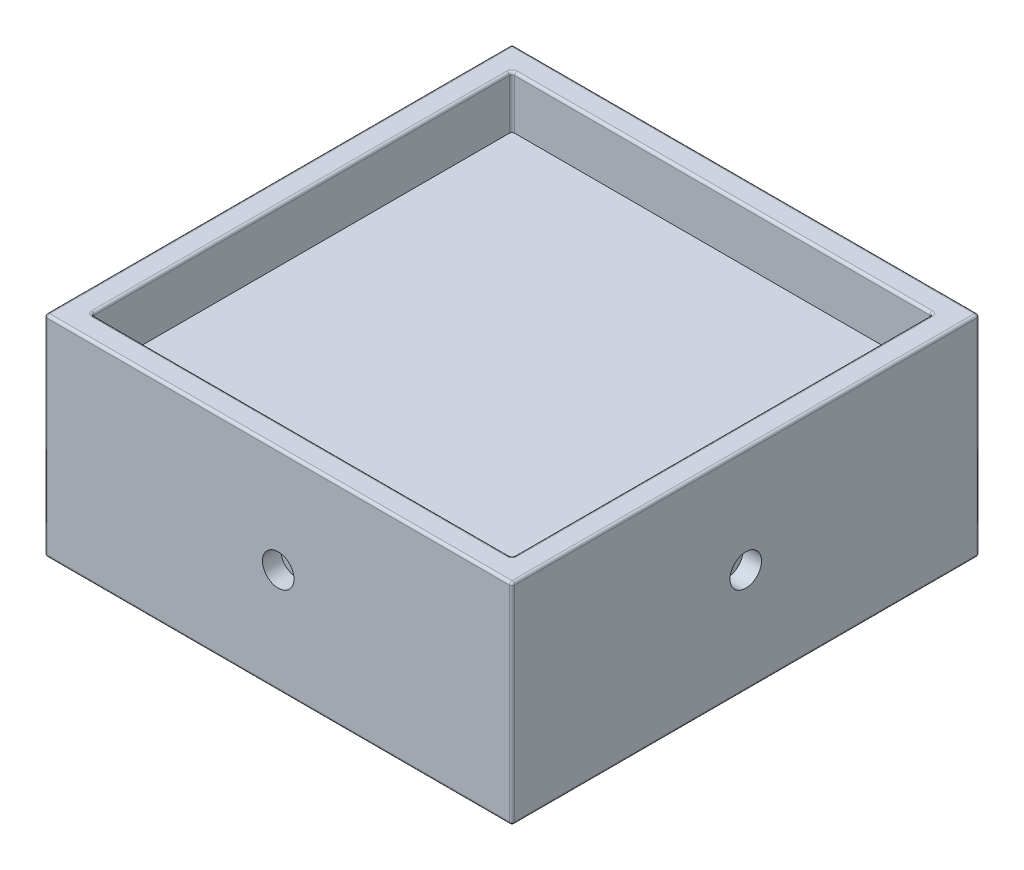
SolidWorks part; units mm, degrees
ref_plane "Front Plane" through (0, 0, 0) normal (0, 0, 1) x (1, 0, 0)
ref_plane "Top Plane" through (0, 0, 0) normal (0, 1, 0) x (1, 0, 0)
ref_plane "Right Plane" through (0, 0, 0) normal (1, 0, 0) x (0, 0, -1)
sketch "Sketch2" plane through (0, 0, 0) normal (0, 1, 0) x (1, 0, 0)
  line L1 (-44.5, 44.5) -> (44.5, 44.5)
  line L2 (-44.5, 44.5) -> (-44.5, -44.5)
  line L3 (-44.5, -44.5) -> (44.5, -44.5)
  line L4 (44.5, 44.5) -> (44.5, -44.5)
  line L5 (-44.5, 44.5) -> (44.5, -44.5) construction
  line L6 (-44.5, -44.5) -> (44.5, 44.5) construction
  point P0 (0, 0)
  dimension "D1" = 89
extrude "Boss-Extrude1" add sketch "Sketch2" along normal blind 40
sketch "Sketch3" plane through (44.5, 0, 0) normal (1, 0, 0) x (0, 0, -1)
  line L0 (-44.5, 0) -> (44.5, 0) construction
  line L1 (-44.5, 40) -> (-44.5, 0) construction
  circle A0 centre (-29.5, 20) radius 3
  dimension "D2" = 6
  dimension "D1" = 20
  dimension "D3" = 15
ref_plane "Plane1" through (0, 0, 0) normal (1, 0, 0) x (0, 0, -1)
sketch "Sketch4" plane through (0, 40, 0) normal (0, 1, 0) x (1, 0, 0)
  line L1 (-40, 40) -> (40, 40)
  line L2 (-40, 40) -> (-40, -40)
  line L3 (-40, -40) -> (40, -40)
  line L4 (40, 40) -> (40, -40)
  line L5 (-40, 40) -> (40, -40) construction
  line L6 (-40, -40) -> (40, 40) construction
  point P0 (0, 0)
  dimension "D1" = 80
ref_plane "Plane2" through (0, 20, 0) normal (0, -1, 0) x (-1, 0, 0)
sketch "Sketch5" plane through (0, 0, 0) normal (0, -1, 0) x (1, 0, 0)
  line L1 (-40, 40) -> (40, 40)
  line L2 (-40, 40) -> (-40, -40)
  line L3 (-40, -40) -> (40, -40)
  line L4 (40, 40) -> (40, -40)
  line L5 (-40, 40) -> (40, -40) construction
  line L6 (-40, -40) -> (40, 40) construction
  point P0 (0, 0)
  dimension "D1" = 80
extrude "Cut-Extrude3" cut sketch "Sketch5" against normal blind 10
extrude "Cut-Extrude5" cut sketch "Sketch4" against normal blind 10
sketch "Sketch6" plane through (44.5, 0, 0) normal (1, 0, 0) x (0, 0, -1)
  line L0 (0, 40) -> (0, 0) construction
  line L1 (-44.5, 40) -> (44.5, 40)
  line L2 (-44.5, 40) -> (-44.5, 0)
  line L3 (-44.5, 0) -> (44.5, 0)
  line L4 (44.5, 40) -> (44.5, 0)
  circle A0 centre (0, 20) radius 3
  dimension "D2" = 6
  dimension "D1" = 20
extrude "Cut-Extrude6" cut sketch "Sketch6" against normal blind 3.5 contours A0 L0 | L0 A0
pattern_circular "CirPattern1" count 4 over 360 about axis through (0, 10, 0) along (0, -1, 0) of "Cut-Extrude6"
fillet "Fillet1" radius 0.5 28 edges at (-40, 5, -40) (40, 5, -40) (40, 5, 40) (-40, 5, 40) (0, 0, 40) (-40, 0, 0) (0, 0, -40) (40, 0, 0) (40, 35, 40) (40, 35, -40) (-40, 35, -40) (-40, 35, 40) (0, 40, 40) (40, 40, 0) (0, 40, -40) (-40, 40, 0) (-44.5, 40, 0) (0, 40, -44.5) (44.5, 40, 0) (44.5, 0, 0) (44.5, 20, -44.5) (0, 0, -44.5) (-44.5, 20, -44.5) (-44.5, 0, 0) (0, 0, 44.5) (-44.5, 20, 44.5) (0, 40, 44.5) (44.5, 20, 44.5)
